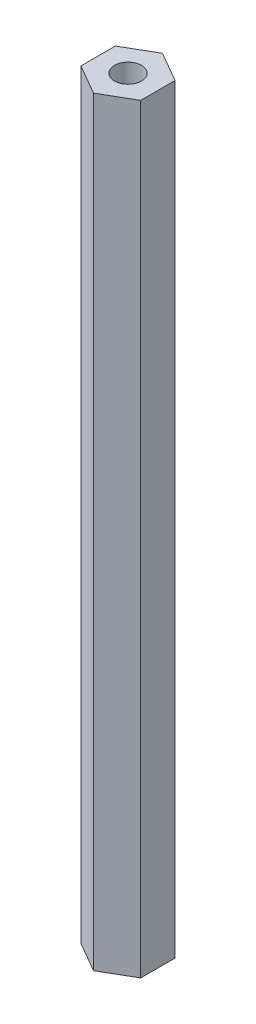
SolidWorks part; units mm, degrees
ref_plane "Front Plane" through (0, 0, 0) normal (0, 0, 1) x (1, 0, 0)
ref_plane "Top Plane" through (0, 0, 0) normal (0, 1, 0) x (1, 0, 0)
ref_plane "Right Plane" through (0, 0, 0) normal (1, 0, 0) x (0, 0, -1)
sketch "Sketch1" plane through (0, 0, 0) normal (0, 1, 0) x (1, 0, 0)
  line L1 (-2.75, 1.5877) -> (-2.75, -1.5877)
  line L2 (-2.75, -1.5877) -> (0, -3.1754)
  line L3 (0, -3.1754) -> (2.75, -1.5877)
  line L4 (2.75, -1.5877) -> (2.75, 1.5877)
  line L5 (2.75, 1.5877) -> (0, 3.1754)
  line L6 (0, 3.1754) -> (-2.75, 1.5877)
  circle A0 centre (0, 0) radius 2.75 construction
  dimension "D1" = 5.5
extrude "Boss-Extrude1" add sketch "Sketch1" along normal blind 70
hole_wizard "M3x0.5 Tapped Hole1" positions "Sketch2" profile "Sketch3" tap size "M3x0.5" standard "ANSI Metric"
sketch "Sketch2" plane through (0, 0, 0) normal (0, -1, 0) x (-1, 0, 0)
  point P0 (0, 0)
sketch "Sketch3" plane through (0, 0, 0) normal (1, 0, 0) x (0, 0, -1)
  line L0 (0, 0) -> (0, 8.2511)
  line L1 (0, 8.2511) -> (1.25, 7.5)
  line L2 (1.25, 7.5) -> (1.25, 0)
  line L5 (1.25, 0) -> (0, 0)
  line L10 (0, 8.2511) -> (-1.25, 7.5) construction
  line L11 (0, -6.35) -> (0, 107.95) construction
  dimension "Tap Drill Dia." = 2.5
  dimension "Tap Drill Depth" = 7.5
  dimension "Drill Angle" = 118
cosmetic thread "Hole Thread1" parameters "D1"=6, "D2"=3
hole_wizard "M3x0.5 Tapped Hole2" positions "Sketch4" profile "Sketch5" tap size "M3x0.5" standard "ANSI Metric"
sketch "Sketch4" plane through (0, 70, 0) normal (0, 1, 0) x (1, 0, 0)
  point P0 (0, 0)
sketch "Sketch5" plane through (0, 70, 0) normal (1, 0, 0) x (0, 0, 1)
  line L0 (0, 0) -> (0, 8.2511)
  line L1 (0, 8.2511) -> (1.25, 7.5)
  line L2 (1.25, 7.5) -> (1.25, 0)
  line L5 (1.25, 0) -> (0, 0)
  line L10 (0, 8.2511) -> (-1.25, 7.5) construction
  line L11 (0, -6.35) -> (0, 107.95) construction
  dimension "Tap Drill Dia." = 2.5
  dimension "Tap Drill Depth" = 7.5
  dimension "Drill Angle" = 118
cosmetic thread "Hole Thread2" parameters "D1"=6, "D2"=3
